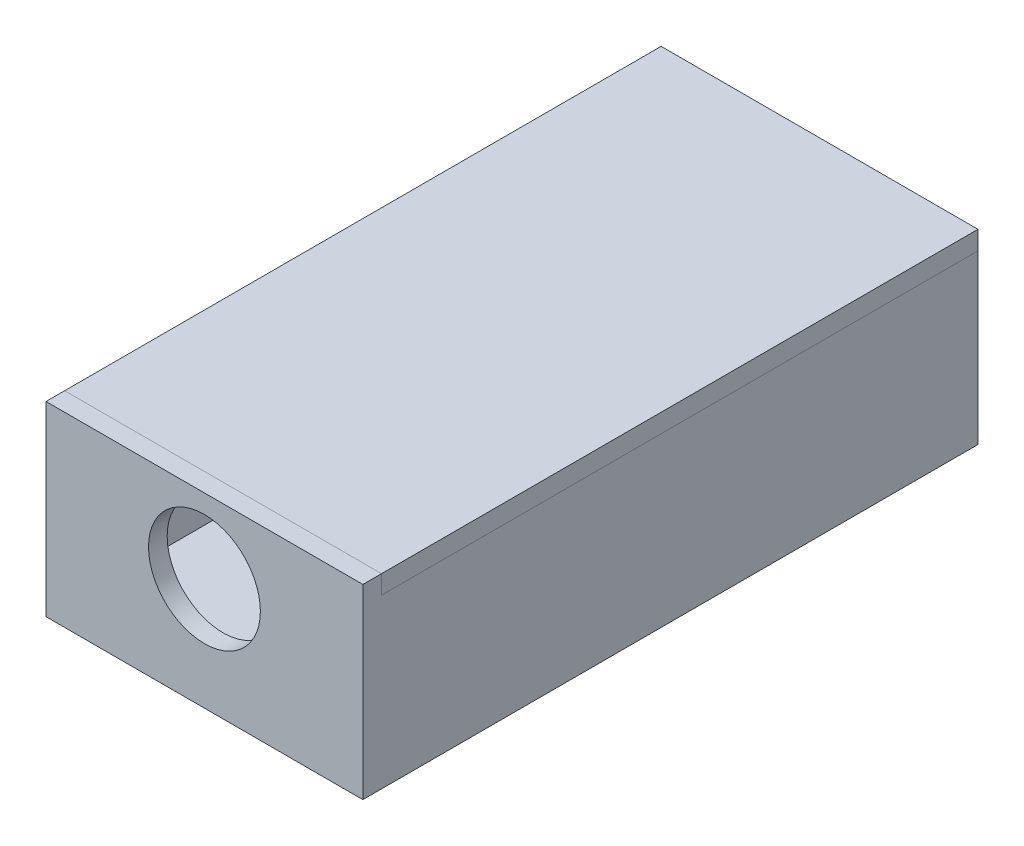
SolidWorks part; units mm, degrees
ref_plane "정면" through (0, 0, 0) normal (0, 0, 1) x (1, 0, 0)
ref_plane "윗면" through (0, 0, 0) normal (0, 1, 0) x (1, 0, 0)
ref_plane "우측면" through (0, 0, 0) normal (1, 0, 0) x (0, 0, -1)
sketch "스케치1" plane through (0, 0, 0) normal (0, 1, 0) x (1, 0, 0)
  line L1 (8.5, -16.5) -> (-8.5, -16.5)
  line L2 (8.5, -16.5) -> (8.5, 16.5)
  line L3 (8.5, 16.5) -> (-8.5, 16.5)
  line L4 (-8.5, -16.5) -> (-8.5, 16.5)
  line L5 (8.5, -16.5) -> (-8.5, 16.5) construction
  line L6 (8.5, 16.5) -> (-8.5, -16.5) construction
  point P0 (0, 0)
  dimension "D1" = 17
  dimension "D2" = 33
extrude "보스-돌출1" add sketch "스케치1" along normal blind 10
sketch "스케치2" plane through (0, 0, 0) normal (0, 1, 0) x (1, 0, 0)
  line L0 (-8.5, 16.5) -> (-8.5, -16.5) construction
  line L1 (-7.5, 16.5) -> (7.5, 16.5)
  line L2 (-7.5, 16.5) -> (-7.5, -15.5)
  line L3 (-7.5, -15.5) -> (7.5, -15.5)
  line L4 (7.5, 16.5) -> (7.5, -15.5)
  line L5 (-8.5, -16.5) -> (8.5, -16.5) construction
  dimension "D1" = 15
  dimension "D2" = 1
  dimension "D3" = 32
  dimension "D4" = 1
extrude "컷-돌출1" cut sketch "스케치2" along normal blind 8 from offset 1
sketch "스케치3" plane through (0, 0, 0) normal (0, 0, 1) x (1, 0, 0)
  line L0 (-8.5, 0) -> (8.5, 0) construction
  circle A0 centre (0, 6) radius 3
  dimension "D1" = 3
  dimension "D2" = 6
extrude "컷-돌출2" cut sketch "스케치3" along normal through all
sketch "스케치5" plane through (0, 0, 0) normal (0, 1, 0) x (1, 0, 0)
  line L0 (8.5, -16.5) -> (8.5, 16.5) construction
  line L1 (-8.5, 16.5) -> (8.5, 16.5)
  line L2 (-8.5, 16.5) -> (-8.5, -15.5)
  line L3 (-8.5, -15.5) -> (8.5, -15.5)
  line L4 (8.5, 16.5) -> (8.5, -15.5)
  line L5 (-8.5, -16.5) -> (8.5, -16.5) construction
  dimension "D1" = 1
extrude "컷-돌출3" cut sketch "스케치5" along normal blind 8 from offset 9
sketch "스케치6" plane through (0, 0, 0) normal (0, 1, 0) x (1, 0, 0)
  line L1 (-8.5, 16.5) -> (8.5, 16.5)
  line L2 (-8.5, 16.5) -> (-8.5, -15.5)
  line L3 (-8.5, -15.5) -> (8.5, -15.5)
  line L4 (8.5, 16.5) -> (8.5, -15.5)
extrude "보스-돌출2" add sketch "스케치6" along normal blind 1 from offset 9 separate body
